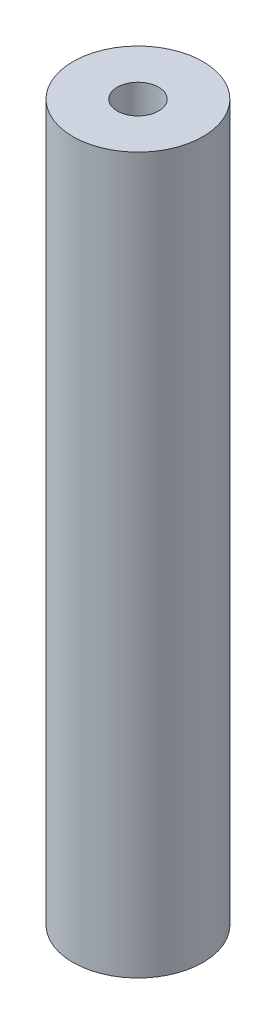
SolidWorks part; units mm, degrees
material "6061-T6 (SS)"
ref_plane "Front Plane" through (0, 0, 0) normal (0, 0, 1) x (1, 0, 0)
ref_plane "Top Plane" through (0, 0, 0) normal (0, 1, 0) x (1, 0, 0)
ref_plane "Right Plane" through (0, 0, 0) normal (1, 0, 0) x (0, 0, -1)
sketch "Sketch1" plane through (0, 0, 0) normal (0, 1, 0) x (1, 0, 0)
  circle A0 centre (0, 0) radius 2.0193
  circle A1 centre (0, 0) radius 6.35
  dimension "D1" = 12.7
  dimension "D2" = 4.0386
extrude "Boss-Extrude1" add sketch "Sketch1" along normal blind 69.85
